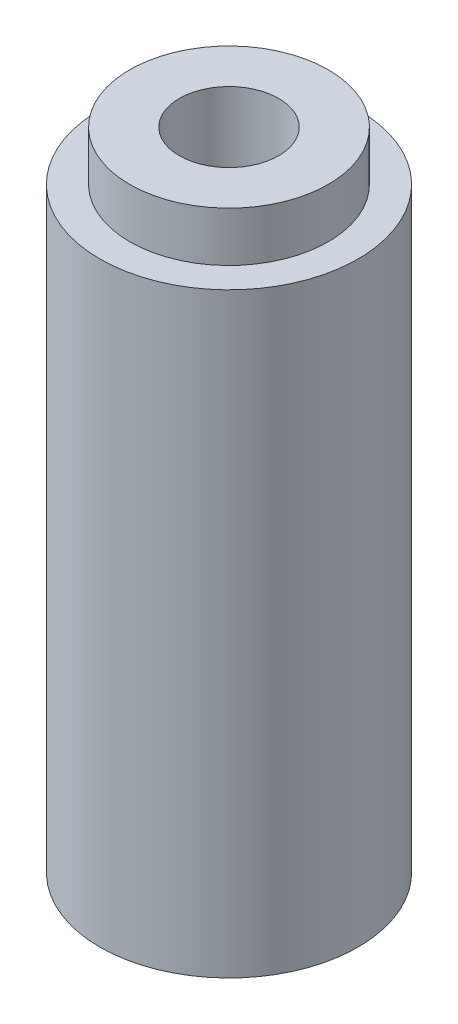
SolidWorks part; units mm, degrees
ref_plane "Спереди" through (0, 0, 0) normal (0, 0, 1) x (1, 0, 0)
ref_plane "Сверху" through (0, 0, 0) normal (0, 1, 0) x (1, 0, 0)
ref_plane "Справа" through (0, 0, 0) normal (1, 0, 0) x (0, 0, -1)
sketch "Эскиз1" plane through (0, 0, 0) normal (0, 1, 0) x (1, 0, 0)
  circle A0 centre (0, 0) radius 2.6
  circle A1 centre (0, 0) radius 1
  dimension "D1" = 5.2
  dimension "D2" = 2
extrude "Бобышка-Вытянуть1" add sketch "Эскиз1" along normal blind 12
sketch "Эскиз3" plane through (0, 12, 0) normal (0, 1, 0) x (1, 0, 0)
  circle A0 centre (0, 0) radius 1
  circle A1 centre (0, 0) radius 2
  circle A2 centre (0, 0) radius 1 construction
  dimension "D1" = 4
extrude "Бобышка-Вытянуть2" add sketch "Эскиз3" along normal blind 1
